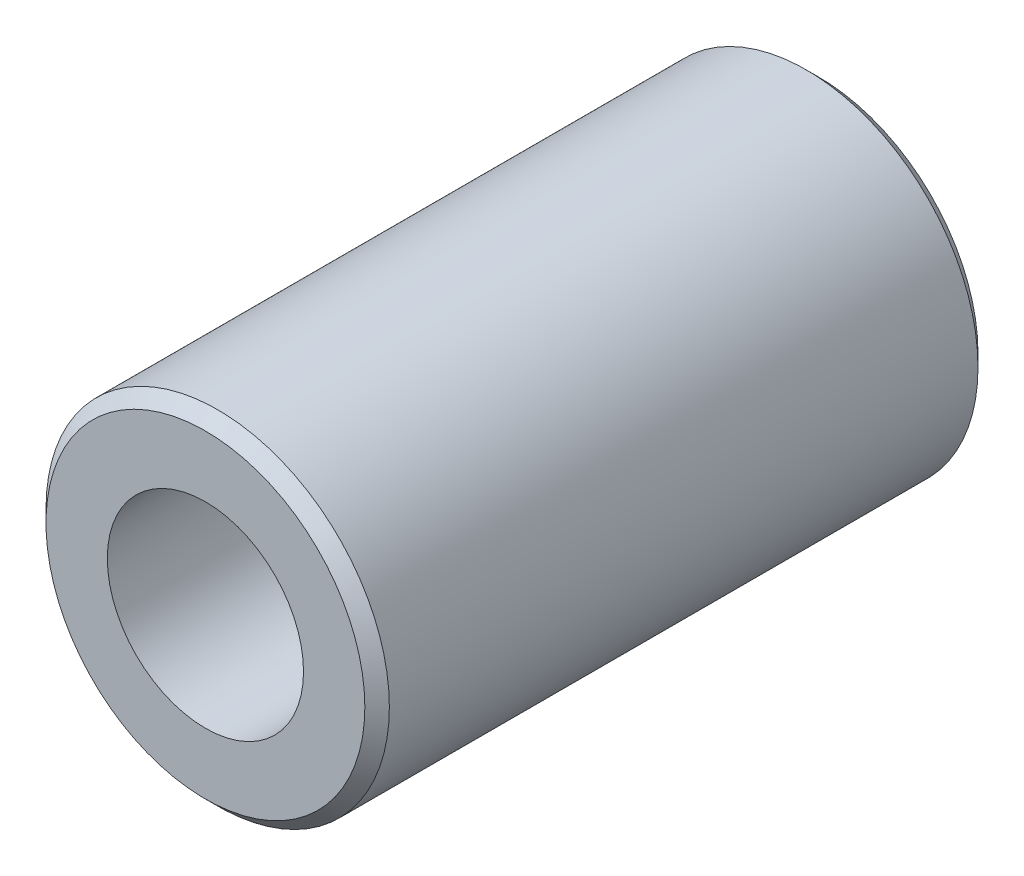
SolidWorks part; units mm, degrees
ref_plane "Front Plane" through (0, 0, 0) normal (0, 0, 1) x (1, 0, 0)
ref_plane "Top Plane" through (0, 0, 0) normal (0, 1, 0) x (1, 0, 0)
ref_plane "Right Plane" through (0, 0, 0) normal (1, 0, 0) x (0, 0, -1)
sketch "Sketch1" plane through (0, 0, 0) normal (0, 0, 1) x (1, 0, 0)
  circle A0 centre (0, 0) radius 7
  dimension "D1" = 14
extrude "Boss-Extrude1" add sketch "Sketch1" along normal blind 25
sketch "Sketch3" plane through (0, 0, 25) normal (0, 0, 1) x (1, 0, 0)
  circle A0 centre (0, 0) radius 4
  dimension "D1" = 8
extrude "Cut-Extrude1" cut sketch "Sketch3" against normal blind 12.5
sketch "Sketch4" plane through (0, 0, 12.5) normal (0, 0, 1) x (1, 0, 0)
  circle A0 centre (0, 0) radius 2.5
  dimension "D1" = 5
extrude "Cut-Extrude2" cut sketch "Sketch4" against normal blind 14.5
chamfer "Chamfer1" distance 0.5 angle 45 2 edges at (7, 0, 0) (7, 0, 25)
